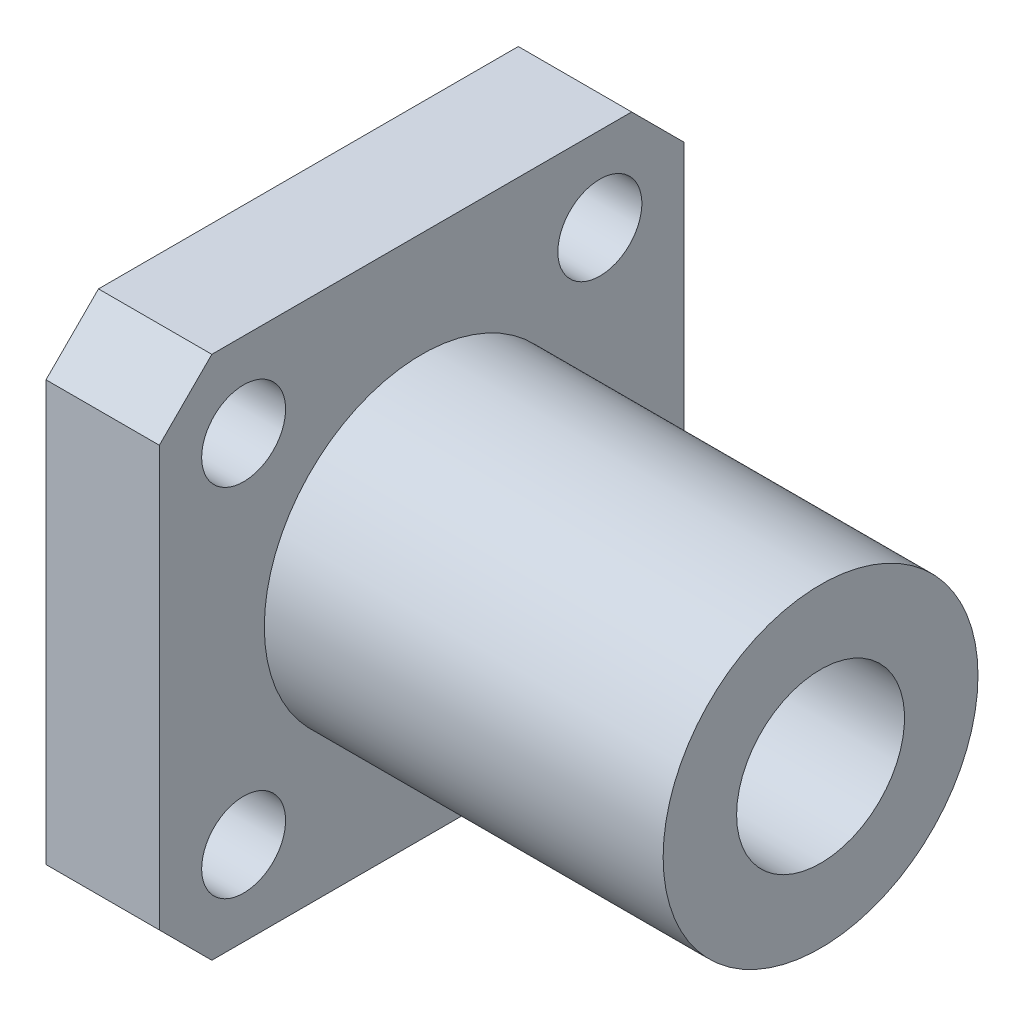
SolidWorks part; units mm, degrees
ref_plane "Front Plane" through (0, 0, 0) normal (0, 0, 1) x (1, 0, 0)
ref_plane "Top Plane" through (0, 0, 0) normal (0, 1, 0) x (1, 0, 0)
ref_plane "Right Plane" through (0, 0, 0) normal (1, 0, 0) x (0, 0, -1)
sketch "Sketch1" plane through (0, 0, 0) normal (1, 0, 0) x (0, 0, -1)
  line L0 (-12.5, 10) -> (-10, 12.5)
  line L1 (-10, 12.5) -> (10, 12.5)
  line L2 (-12.5, 10) -> (-12.5, -10)
  line L3 (-10, -12.5) -> (10, -12.5)
  line L4 (12.5, 10) -> (12.5, -10)
  line L5 (-12.5, 12.5) -> (12.5, -12.5) construction
  line L6 (-12.5, -12.5) -> (12.5, 12.5) construction
  line L7 (-12.5, -10) -> (-10, -12.5)
  line L8 (10, -12.5) -> (12.5, -10)
  line L9 (10, 12.5) -> (12.5, 10)
  circle A0 centre (0, 0) radius 4
  circle A1 centre (8.4853, 8.4853) radius 2
  circle A2 centre (8.4853, -8.4853) radius 2
  circle A3 centre (-8.4853, -8.4853) radius 2
  circle A4 centre (-8.4853, 8.4853) radius 2
  point P0 (0, 0)
  point P27 (0, 0)
  dimension "D3" = 8
  dimension "D5" = 4
  dimension "D1" = 25
  dimension "D2" = 25
  dimension "D4" = 12
  dimension "D10" = 4
extrude "Boss-Extrude1" add sketch "Sketch1" along normal blind 5.4
sketch "Sketch2" plane through (5.4, 0, 0) normal (1, 0, 0) x (0, 0, -1)
  circle A0 centre (0, 0) radius 7.5
  circle A1 centre (0, 0) radius 4 construction
  circle A2 centre (0, 0) radius 4
  dimension "D1" = 15
extrude "Boss-Extrude2" add sketch "Sketch2" along normal blind 19
